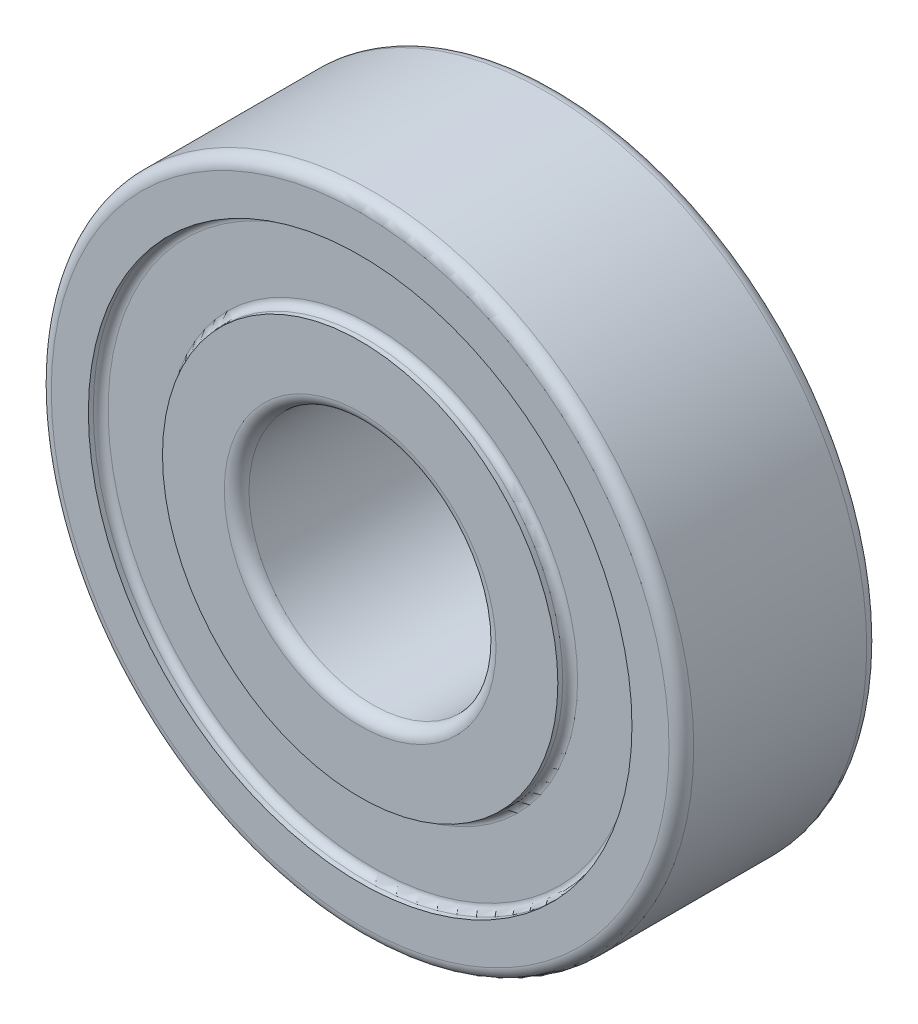
SolidWorks part; units mm, degrees
ref_plane "Ebene vorne" through (0, 0, 0) normal (0, 0, 1) x (1, 0, 0)
ref_plane "Ebene oben" through (0, 0, 0) normal (0, 1, 0) x (1, 0, 0)
ref_plane "Ebene rechts" through (0, 0, 0) normal (1, 0, 0) x (0, 0, -1)
sketch "Skizze1" plane through (0, 0, 0) normal (0, 0, 1) x (1, 0, 0)
  circle A0 centre (0, 0) radius 13
  circle A1 centre (0, 0) radius 5
extrude "Aufsatz-Linear austragen1" add sketch "Skizze1" along normal blind 8
fillet "Verrundung1" radius 0.5 4 edges at (5, 0, 0) (13, 0, 0) (5, 0, 8) (13, 0, 8)
sketch "Skizze2" plane through (0, 0, 0) normal (0, 0, -1) x (-1, 0, 0)
  circle A0 centre (0, 0) radius 11
  circle A1 centre (0, 0) radius 8
  dimension "D1" = 16
  dimension "D2" = 22
extrude "Schnitt-Linear austragen1" cut sketch "Skizze2" against normal blind 0.5
sketch "Skizze3" plane through (0, 0, 8) normal (0, 0, 1) x (1, 0, 0)
  circle A0 centre (0, 0) radius 8
  circle A1 centre (0, 0) radius 11
extrude "Schnitt-Linear austragen2" cut sketch "Skizze3" against normal blind 0.5
fillet "Verrundung2" radius 0.3 4 edges at (11, 0, 7.5) (8, 0, 7.5) (-11, 0, 0.5) (-8, 0, 0.5)
